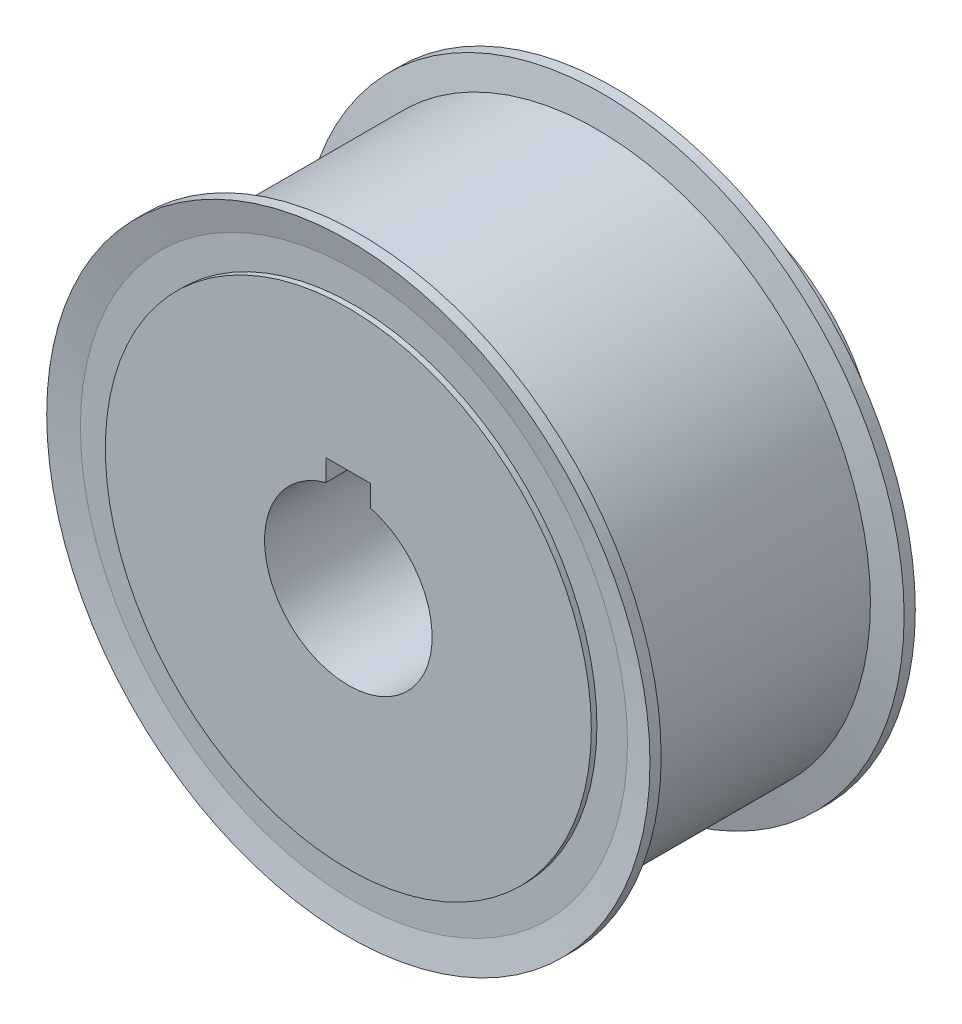
SolidWorks part; units mm, degrees
ref_plane "Front" through (0, 0, 0) normal (0, 0, 1) x (1, 0, 0)
ref_plane "Top" through (0, 0, 0) normal (0, 1, 0) x (1, 0, 0)
ref_plane "Right" through (0, 0, 0) normal (1, 0, 0) x (0, 0, -1)
sketch "Sketch1" plane through (0, 0, 0) normal (1, 0, 0) x (0, 0, -1)
  line L0 (-66.1429, 0) -> (13.5853, 0) construction
  line L1 (-65, 43.5) -> (-64, 43.5)
  line L2 (-65, 43.5) -> (-65, 0)
  line L3 (-65, 0) -> (0, 0)
  line L4 (-18.5, 43.5) -> (-17.5, 43.5)
  line L5 (-64, 43.5) -> (-64, 48.965)
  line L6 (-64, 48.965) -> (-65, 54)
  line L7 (-65, 54) -> (-63, 54)
  line L8 (-63, 54) -> (-62, 48.965)
  line L9 (-62, 48.965) -> (-20.5, 48.965)
  line L10 (-20.5, 48.965) -> (-19.5, 54)
  line L11 (-19.5, 54) -> (-17.5, 54)
  line L12 (-17.5, 54) -> (-18.5, 48.965)
  line L13 (-18.5, 48.965) -> (-18.5, 43.5)
  line L14 (-17.5, 43.5) -> (-17.5, 30)
  line L15 (-17.5, 30) -> (0, 30)
  line L16 (0, 30) -> (0, 0)
  dimension "D1" = 87
  dimension "D2" = 97.93
  dimension "D3" = 108
  dimension "D4" = 17.5
  dimension "D5" = 2
  dimension "D6" = 3
  dimension "D7" = 65
  dimension "D8" = 60
revolve "Revolve1" add sketch "Sketch1" angle 360 about L0
sketch "Sketch2" plane through (0, 0, 0) normal (1, 0, 0) x (0, 0, -1)
  line L0 (15.3565, 0) -> (-72.5332, 0) construction
  line L1 (-65, 54) -> (-65, -54) construction
  line L2 (-65, 15) -> (0, 15)
  line L3 (-65, 15) -> (-65, 0)
  line L4 (-65, 0) -> (0, 0)
  line L5 (0, 15) -> (0, 0)
  dimension "D1" = 30
revolve "Cut-Revolve1" cut sketch "Sketch2" angle 360 about L0
sketch "Sketch3" plane through (0, 0, 65) normal (0, 0, 1) x (1, 0, 0)
  line L0 (0, 0) -> (0, 24.8792) construction
  line L1 (-4, 18.3) -> (4, 18.3)
  line L2 (-4, 18.3) -> (-4, 14.4568)
  line L4 (4, 18.3) -> (4, 14.4568)
  circle A0 centre (0, 0) radius 15 construction
  arc A1 (4, 14.4568) -> (-4, 14.4568) centre (0, 0) ccw
  dimension "D1" = 18.3
  dimension "D2" = 8
extrude "Cut-Extrude1" cut sketch "Sketch3" against normal through all
ref_plane "Plane1" through (0, 30, 0) normal (0, 1, 0) x (-1, 0, 0)
hole_wizard "M6x1.0 Tapped Hole1" positions "Sketch7" profile "Sketch6" tap size "M6x1.0" standard "JIS"
sketch "Sketch7" plane through (0, 30, -41.25) normal (0, 1, 0) x (-1, 0, 0)
  line L0 (-30, 41.25) -> (30, 41.25) construction
  point P0 (0, 49.25)
  dimension "D1" = 8
cosmetic thread "Hole Thread1" parameters "D2"=6
sketch "Sketch6" plane through (0, 30, 8) normal (1, 0, 0) x (0, 0, 1)
  line L0 (0, 0) -> (0, 60)
  line L1 (0, 60) -> (2.5, 60)
  line L2 (2.5, 60) -> (2.5, 0)
  line L5 (2.5, 0) -> (0, 0)
  line L11 (0, -6.35) -> (0, 107.95) construction
  dimension "Thru Tap Drill Dia." = 5
  dimension "Thru Tap Drill Depth" = 60
pattern_circular "CirPattern1" count 2 over 120 about axis through (0, 0, -15.3565) along (0, 0, -1) of "M6x1.0 Tapped Hole1"
